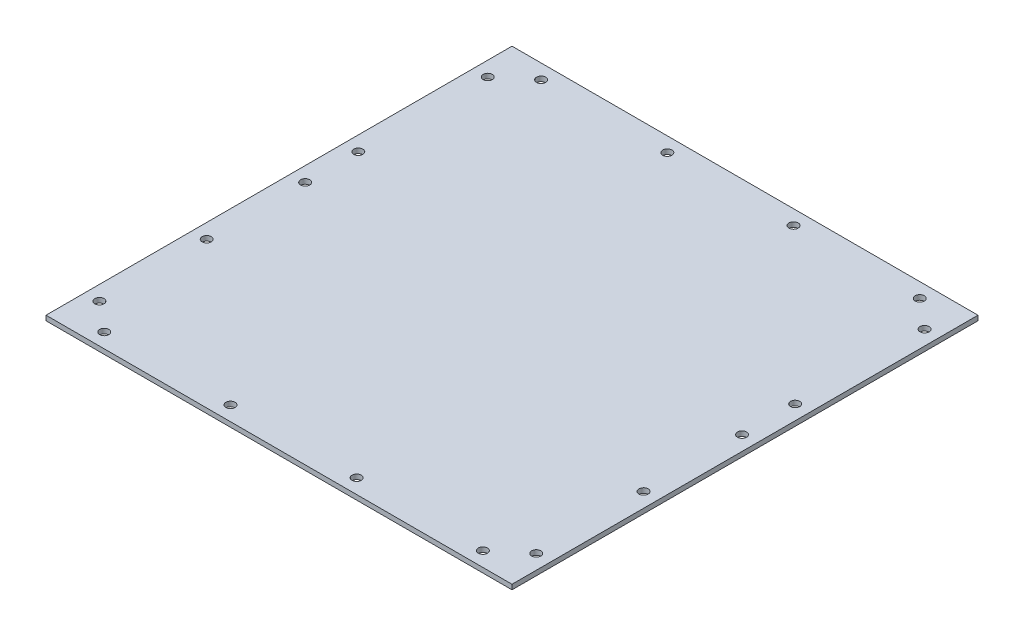
SolidWorks part; units mm, degrees
material "Thornel VCB-20 Carbon Cloth"
ref_plane "Front Plane" through (0, 0, 0) normal (0, 0, 1) x (1, 0, 0)
ref_plane "Top Plane" through (0, 0, 0) normal (0, 1, 0) x (1, 0, 0)
ref_plane "Right Plane" through (0, 0, 0) normal (1, 0, 0) x (0, 0, -1)
sketch "Sketch2" plane through (0, 0, 0) normal (0, 1, 0) x (1, 0, 0)
  line L0 (0, 0) -> (152.4, 0)
  line L1 (152.4, 0) -> (152.4, 152.4)
  line L2 (152.4, 152.4) -> (0, 152.4)
  line L3 (0, 152.4) -> (0, 0)
  dimension "D1" = 152.4
  dimension "D2" = 152.4
extrude "Boss-Extrude1" add sketch "Sketch2" along normal blind 1.5875
sketch "Sketch3" plane through (0, 1.5875, 0) normal (0, 1, 0) x (1, 0, 0)
  line L0 (0, 152.4) -> (4.7625, 152.4)
  line L1 (152.4, 152.4) -> (0, 152.4) construction
  line L2 (4.7625, 152.4) -> (4.7625, 0)
  line L3 (0, 0) -> (152.4, 0) construction
  line L4 (0, 152.4) -> (0, 147.6375)
  line L5 (0, 152.4) -> (0, 0) construction
  line L6 (0, 147.6375) -> (152.4, 147.6375)
  line L7 (152.4, 0) -> (152.4, 152.4) construction
  line L8 (152.4, 152.4) -> (147.6375, 152.4)
  line L9 (147.6375, 152.4) -> (147.6375, 0)
  line L10 (152.4, 0) -> (152.4, 4.7625)
  line L11 (152.4, 4.7625) -> (0, 4.7625)
  point P21 (4.7625, 139.7)
  point P23 (14.2875, 147.6375)
  point P24 (147.6375, 139.7)
  point P25 (138.1125, 4.7625)
  point P26 (4.7625, 12.7)
  dimension "D1" = 4.7625
  dimension "D2" = 4.7625
  dimension "D3" = 4.7625
  dimension "D4" = 4.7625
  dimension "D5" = 12.7
  dimension "D6" = 14.2875
  dimension "D7" = 12.7
  dimension "D8" = 14.2875
  dimension "D9" = 12.7
sketch "Sketch4" plane through (0, 1.5875, 0) normal (0, 1, 0) x (1, 0, 0)
  point P0 (14.2875, 147.6375)
  point P3 (147.6375, 139.7)
  point P6 (138.1125, 4.7625)
  point P9 (4.7625, 12.7)
sketch "Sketch6" plane through (0, 1.5875, 0) normal (0, 1, 0) x (1, 0, 0)
  line L0 (152.4, 4.7625) -> (0, 4.7625) construction
  line L1 (0, 152.4) -> (0, 0) construction
  point P0 (14.2875, 147.6375)
  point P3 (14.2875, 4.7625)
  dimension "D1" = 14.2875
hole_wizard "Ø3.0mm Dowel Hole2" positions "Sketch6" profile "Sketch7" hole size "Ø3.0" standard "ANSI Metric" end condition through all
sketch "Sketch7" plane through (14.2875, 1.5875, -147.6375) normal (1, 0, 0) x (0, 0, 1)
  line L0 (0, 0) -> (0, 1.5875)
  line L1 (0, 1.5875) -> (1.5, 1.5875)
  line L2 (1.5, 1.5875) -> (1.5, 0)
  line L5 (1.5, 0) -> (0, 0)
  line L11 (0, -6.35) -> (0, 107.95) construction
  dimension "Thru Hole Dia." = 3
  dimension "Thru Hole Depth" = 1.5875
sketch "Sketch8" plane through (0, 1.5875, 0) normal (0, 1, 0) x (1, 0, 0)
  point P0 (4.7625, 139.7)
  point P3 (147.6375, 139.7)
hole_wizard "Ø3.0mm Dowel Hole3" positions "Sketch8" profile "Sketch9" hole size "Ø3.0" standard "ANSI Metric" end condition through all
sketch "Sketch9" plane through (4.7625, 1.5875, -139.7) normal (1, 0, 0) x (0, 0, 1)
  line L0 (0, 0) -> (0, 1.5875)
  line L1 (0, 1.5875) -> (1.5, 1.5875)
  line L2 (1.5, 1.5875) -> (1.5, 0)
  line L5 (1.5, 0) -> (0, 0)
  line L11 (0, -6.35) -> (0, 107.95) construction
  dimension "Thru Hole Dia." = 3
  dimension "Thru Hole Depth" = 1.5875
pattern_linear "LPattern1" count 4 spacing 42.3333 along (0, 0, 1) skipping (2, 0) of "Ø3.0mm Dowel Hole3"
pattern_linear "LPattern2" count 4 spacing 41.275 along (1, 0, 0) of "Ø3.0mm Dowel Hole2"
sketch "Sketch10" plane through (0, 1.5875, 0) normal (0, 1, 0) x (1, 0, 0)
  line L1 (0, 0) -> (152.4, 0) construction
  point P1 (147.6375, 47.79)
  point P5 (147.6375, 80)
  dimension "D1" = 32.21
  dimension "D2" = 80
hole_wizard "Ø3.0mm Dowel Hole1" positions "Sketch10" profile "Sketch11" hole size "Ø3.0" standard "ANSI Metric" end condition through all
sketch "Sketch11" plane through (147.6375, 1.5875, -47.79) normal (1, 0, 0) x (0, 0, 1)
  line L0 (0, 0) -> (0, 1.5875)
  line L1 (0, 1.5875) -> (1.5, 1.5875)
  line L2 (1.5, 1.5875) -> (1.5, 0)
  line L5 (1.5, 0) -> (0, 0)
  line L11 (0, -6.35) -> (0, 107.95) construction
  dimension "Thru Hole Dia." = 3
  dimension "Thru Hole Depth" = 1.5875
ref_plane "Plane1" through (76.2, 0, 0) normal (1, 0, 0) x (0, 0, -1)
mirror "Mirror1" about plane through (76.2, 0, 0) normal (1, 0, 0) of "Ø3.0mm Dowel Hole1"
